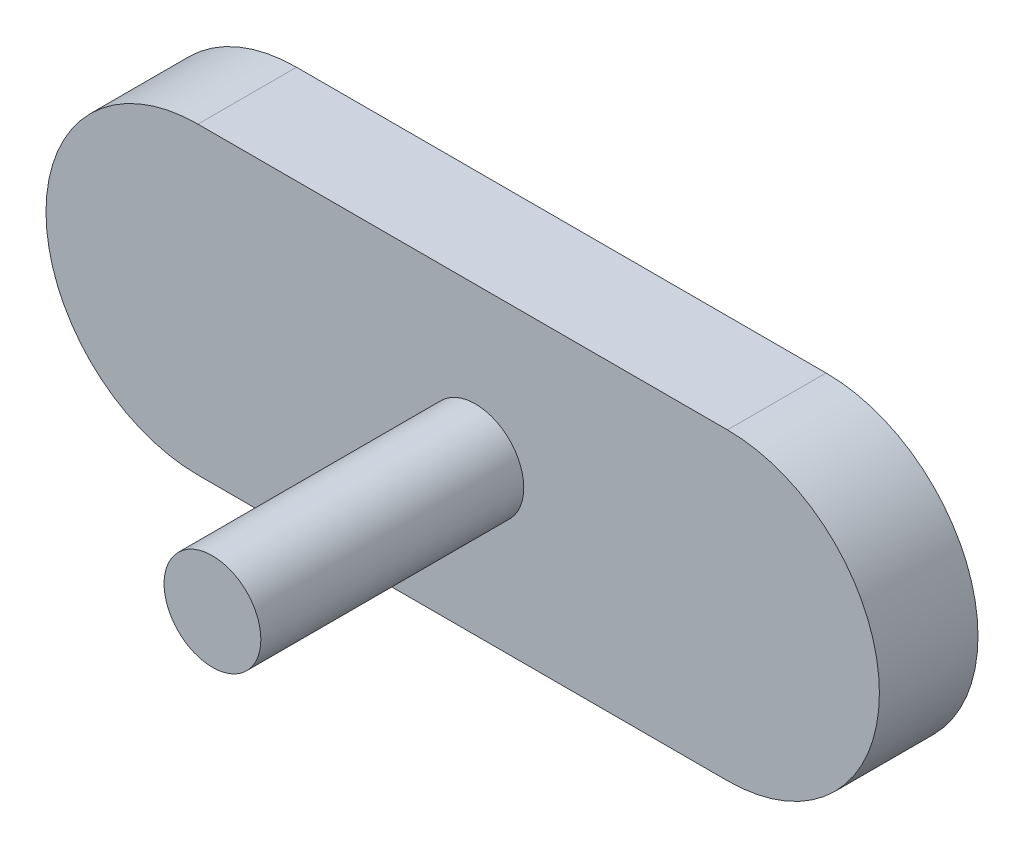
SolidWorks part; units mm, degrees
ref_plane "前视基准面" through (0, 0, 0) normal (0, 0, 1) x (1, 0, 0)
ref_plane "上视基准面" through (0, 0, 0) normal (0, 1, 0) x (1, 0, 0)
ref_plane "右视基准面" through (0, 0, 0) normal (1, 0, 0) x (0, 0, -1)
other "Configuration Table"
sketch "草图1" plane through (0, 0, 0) normal (0, 0, 1) x (1, 0, 0)
  line L0 (-8.4417, 0) -> (7.6708, 0) construction
  line L1 (-8.4417, 4.6236) -> (7.6708, 4.6236)
  line L2 (-8.4417, -4.6236) -> (7.6708, -4.6236)
  arc A0 (-8.4417, 4.6236) -> (-8.4417, -4.6236) centre (-8.4417, 0) ccw
  arc A1 (7.6708, -4.6236) -> (7.6708, 4.6236) centre (7.6708, 0) ccw
  point P3 (-0.3855, 0)
extrude "凸台-拉伸1" add sketch "草图1" along normal blind 3
sketch "草图2" plane through (0, 0, 3) normal (0, 0, 1) x (1, 0, 0)
  circle A0 centre (0, 0) radius 1.4723
extrude "凸台-拉伸2" add sketch "草图2" along normal blind 8
